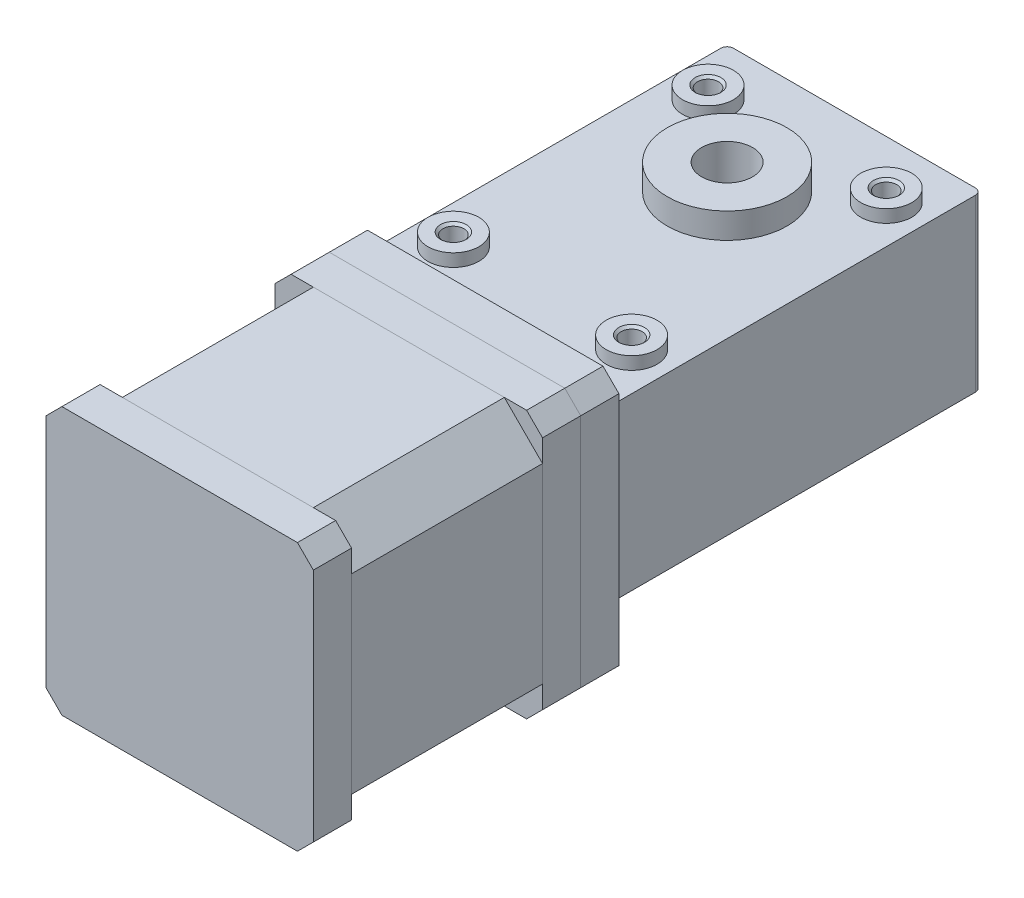
SolidWorks part; units mm, degrees
ref_plane "정면" through (0, 0, 0) normal (0, 0, 1) x (1, 0, 0)
ref_plane "윗면" through (0, 0, 0) normal (0, 1, 0) x (1, 0, 0)
ref_plane "우측면" through (0, 0, 0) normal (1, 0, 0) x (0, 0, -1)
sketch "스케치1" plane through (0, 0, 0) normal (0, 0, 1) x (1, 0, 0)
  line L1 (-21, 21) -> (21, 21)
  line L2 (-21, 21) -> (-21, -21)
  line L3 (-21, -21) -> (21, -21)
  line L4 (21, 21) -> (21, -21)
  line L5 (-21, 21) -> (21, -21) construction
  line L6 (-21, -21) -> (21, 21) construction
  point P0 (0, 0)
  dimension "D1" = 42
  dimension "D2" = 42
extrude "보스-돌출1" add sketch "스케치1" along normal blind 42
ref_plane "평면1" through (0, 0, 36) normal (0, 0, 1) x (1, 0, 0)
ref_plane "평면2" through (0, 0, 6) normal (0, 0, -1) x (-1, 0, 0)
split line "분할선1"
sketch "스케치2" plane through (0, 0, 36) normal (0, 0, 1) x (1, 0, 0)
  line L0 (-21, -21) -> (-15, -21)
  line L1 (-21, -21) -> (21, -21) construction
  line L2 (-15, -21) -> (-21, -15)
  line L3 (-21, 21) -> (-21, -21) construction
  line L4 (-21, -15) -> (-21, -21)
  line L5 (-21, 21) -> (-21, 15)
  line L6 (-21, 15) -> (-15, 21)
  line L7 (-15, 21) -> (-21, 21)
  line L8 (21, 21) -> (15, 21)
  line L9 (15, 21) -> (21, 15)
  line L10 (21, 15) -> (21, 21)
  line L11 (21, -21) -> (21, -15)
  line L12 (21, -15) -> (15, -21)
  line L13 (15, -21) -> (21, -21)
  point P20 (0, 0)
  dimension "D1" = 6
  dimension "D2" = 6
  dimension "D3" = 4
extrude "컷-돌출1" cut sketch "스케치2" against normal blind 30
chamfer "모따기2" distance 2.5 angle 45 8 edges at (-21, 21, 3) (-21, 21, 39) (-21, -21, 39) (-21, -21, 3) (21, -21, 3) (21, -21, 39) (21, 21, 3) (21, 21, 39)
sketch "스케치3" plane through (0, 0, 0) normal (0, 0, -1) x (-1, 0, 0)
  line L0 (-18.5, 21) -> (-21, 18.5)
  line L1 (-21, 18.5) -> (-21, -18.5)
  line L2 (-21, -18.5) -> (-18.5, -21)
  line L3 (-18.5, -21) -> (18.5, -21)
  line L4 (18.5, -21) -> (21, -18.5)
  line L5 (21, -18.5) -> (21, 18.5)
  line L6 (21, 18.5) -> (18.5, 21)
  line L7 (18.5, 21) -> (-18.5, 21)
extrude "보스-돌출2" add sketch "스케치3" along normal blind 6
ref_plane "평면3" through (0, 0, 0) normal (0, 0, -1) x (-1, 0, 0)
split line "분할선2"
sketch "스케치4" plane through (0, 0, -6) normal (0, 0, -1) x (-1, 0, 0)
  line L0 (18.5, 21) -> (-18.5, 21) construction
  line L1 (-20, 16.5) -> (20, 16.5)
  line L2 (-20, 16.5) -> (-20, -10.3)
  line L3 (-20, -10.3) -> (20, -10.3)
  line L4 (20, 16.5) -> (20, -10.3)
  line L5 (-20, 16.5) -> (20, -10.3) construction
  line L6 (-20, -10.3) -> (20, 16.5) construction
  point P0 (0, 3.1)
  dimension "D1" = 40
  dimension "D2" = 0
  dimension "D3" = 26.8
  dimension "D4" = 4.5
extrude "보스-돌출3" add sketch "스케치4" along normal blind 58
sketch "스케치5" plane through (0, 16.5, 0) normal (0, 1, 0) x (1, 0, 0)
  line L0 (-19, 64) -> (-20, 64)
  line L1 (-19, 64) -> (19, 64)
  line L2 (-20, 63) -> (-20, 7)
  line L3 (-19, 6) -> (19, 6)
  line L4 (20, 63) -> (20, 7)
  line L5 (-20, 64) -> (-20, 63)
  line L6 (19, 64) -> (20, 64)
  line L7 (20, 64) -> (20, 63)
  line L8 (20, 7) -> (20, 6)
  line L9 (20, 6) -> (19, 6)
  line L10 (-20, 7) -> (-20, 6)
  line L11 (-20, 6) -> (-19, 6)
  arc A0 (19, 6) -> (20, 7) centre (19, 7) ccw
  arc A1 (19, 64) -> (20, 63) centre (19, 63) cw
  arc A2 (-19, 64) -> (-20, 63) centre (-19, 63) ccw
  arc A3 (-20, 7) -> (-19, 6) centre (-19, 7) ccw
  point P8 (20, 6)
  point P13 (-20, 64)
  line M9 (-20, 6) -> (20, 6)
  line M10 (20, 6) -> (20, 64)
  line M11 (20, 64) -> (-20, 64)
  line M12 (-20, 64) -> (-20, 6)
  dimension "D1" = 1
extrude "컷-돌출2" cut sketch "스케치5" against normal blind 58 contours A3 M12 M9 | A0 M9 M10 | A1 M11 M10 | A2 M11 M12 | L8 L9
sketch "스케치6" plane through (0, 16.5, 0) normal (0, 1, 0) x (1, 0, 0)
  line L0 (-19, 64) -> (19, 64) construction
  circle A0 centre (0, 44) radius 9.4
  dimension "D1" = 18.8
  dimension "D2" = 20
extrude "보스-돌출4" add sketch "스케치6" along normal blind 4
sketch "스케치7" plane through (0, 16.5, 0) normal (0, 1, 0) x (1, 0, 0)
  circle A0 centre (14, 55) radius 4
  circle A1 centre (-14, 55) radius 4
  circle A2 centre (-14, 15) radius 4
  circle A3 centre (14, 15) radius 4
  circle A4 centre (0, 44) radius 9.4 construction
  circle A5 centre (0, 44) radius 9.4 construction
  point P12 (1.6161, 53.26)
  dimension "D3" = 14
  dimension "D5" = 8
  dimension "D6" = 8
  dimension "D7" = 8
  dimension "D8" = 8
  dimension "D11" = 40
  dimension "D1" = 11
  dimension "D2" = 11
  dimension "D4" = 14
  dimension "D9" = 28
  dimension "D10" = 14
  dimension "D12" = 40
extrude "보스-돌출5" add sketch "스케치7" along normal blind 2
sketch "스케치8" plane through (0, 20.5, 0) normal (0, 1, 0) x (1, 0, 0)
  circle A0 centre (0, 44) radius 4
  dimension "D1" = 8
extrude "컷-돌출3" cut sketch "스케치8" against normal blind 14
hole_wizard "M4 나사 구멍1" positions "스케치9" profile "스케치10" tap size "M4" standard "KS"
sketch "스케치9" plane through (0, 18.5, 0) normal (0, 1, 0) x (1, 0, 0)
  point P0 (-14, 55)
  point P3 (14, 55)
  point P6 (14, 15)
  point P9 (-14, 15)
sketch "스케치10" plane through (-14, 18.5, -55) normal (1, 0, 0) x (0, 0, 1)
  line L0 (0, 0) -> (0, 12.4914)
  line L1 (0, 12.4914) -> (1.65, 11.5)
  line L2 (1.65, 11.5) -> (1.65, 0.375)
  line L3 (1.65, 0.375) -> (2.025, 0)
  line L5 (2.025, 0) -> (0, 0)
  line L6 (-1.65, 0.375) -> (-2.025, 0) construction
  line L10 (0, 12.4914) -> (-1.65, 11.5) construction
  line L11 (0, -6.35) -> (0, 107.95) construction
  dimension "탭 드릴 지름" = 3.3
  dimension "탭 드릴 깊이" = 11.5
  dimension "표면 카운터싱크 지름" = 4.05
  dimension "표면 카운터싱크 각도" = 90
  dimension "드릴 각도" = 118
cosmetic thread "구멍 나사산1" parameters "D1"=8, "D2"=4
cosmetic thread "구멍 나사산2" parameters "D1"=8, "D2"=4
cosmetic thread "구멍 나사산3" parameters "D1"=8, "D2"=4
cosmetic thread "구멍 나사산4" parameters "D1"=8, "D2"=4
ref_plane "평면4" through (0, 3.1, 0) normal (0, 1, 0) x (1, 0, 0)
mirror "대칭 복사1" about plane through (0, 3.1, 0) normal (0, 1, 0) of "M4 나사 구멍1", "보스-돌출5", "보스-돌출4"
cosmetic thread "구멍 나사산5" parameters "D1"=8, "D2"=4
cosmetic thread "구멍 나사산6" parameters "D1"=8, "D2"=4
cosmetic thread "구멍 나사산7" parameters "D1"=8, "D2"=4
cosmetic thread "구멍 나사산8" parameters "D1"=8, "D2"=4
sketch "스케치11" plane through (0, -14.3, 0) normal (0, -1, 0) x (1, 0, 0)
  circle A0 centre (0, -44) radius 9.4
extrude "컷-돌출4" cut sketch "스케치11" against normal blind 0.1
